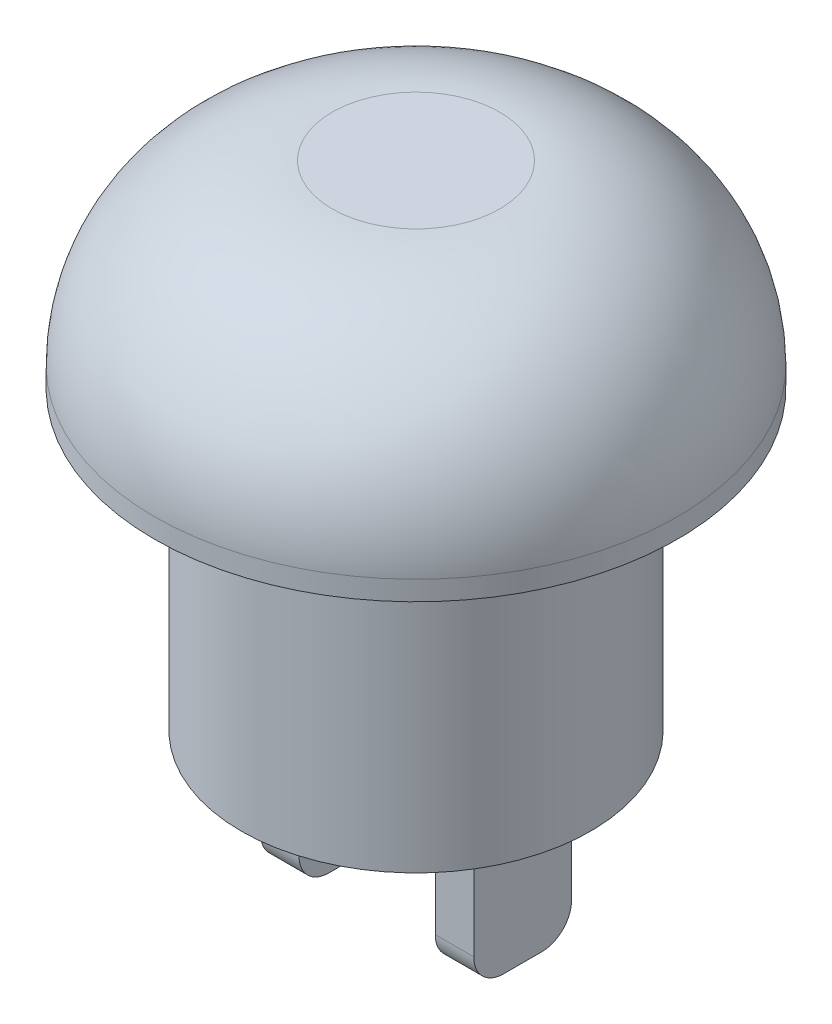
SolidWorks part; units mm, degrees
ref_plane "Plan de face" through (0, 0, 0) normal (0, 0, 1) x (1, 0, 0)
ref_plane "Plan de dessus" through (0, 0, 0) normal (0, 1, 0) x (1, 0, 0)
ref_plane "Plan de droite" through (0, 0, 0) normal (1, 0, 0) x (0, 0, -1)
sketch "Sketch1" plane through (0, 0, 0) normal (0, 1, 0) x (1, 0, 0)
  circle A0 centre (0, 0) radius 5.9
  dimension "D1" = 11.8
extrude "Boss-Extrude1" add sketch "Sketch1" along normal blind 10
sketch "Sketch2" plane through (0, 10, 0) normal (0, 1, 0) x (1, 0, 0)
  circle A0 centre (0, 0) radius 8.83
  dimension "D1" = 17.66
extrude "Boss-Extrude2" add sketch "Sketch2" along normal blind 6.66
fillet "Fillet1" radius 6 1 edges at (0, 16.66, 8.83)
sketch "Sketch3" plane through (0, 0, 0) normal (0, -1, 0) x (1, 0, 0)
  line L0 (-5.9, 0) -> (5.9, 0)
  line L1 (-5.9, 0) -> (0, 0) construction
  line L2 (0, -5.1238) -> (0, 5.1238)
  line L3 (-3.6, -1.65) -> (-2.3, -1.65)
  line L4 (-3.6, -1.65) -> (-3.6, 1.65)
  line L5 (-3.6, 1.65) -> (-2.3, 1.65)
  line L6 (-2.3, -1.65) -> (-2.3, 1.65)
  line L7 (-3.6, -1.65) -> (-2.3, 1.65) construction
  line L8 (-3.6, 1.65) -> (-2.3, -1.65) construction
  line L9 (3.6, 1.65) -> (2.3, 1.65)
  line L10 (2.3, -1.65) -> (2.3, 1.65)
  line L11 (3.6, -1.65) -> (2.3, -1.65)
  line L12 (3.6, -1.65) -> (3.6, 1.65)
  circle A0 centre (0, 0) radius 5.9 construction
  point P0 (-2.95, 0)
  point P7 (0, 0)
  point P16 (0, 0)
  dimension "D1" = 1.3
  dimension "D2" = 3.3
extrude "Boss-Extrude3" add sketch "Sketch3" along normal blind 5 contours L11 L12 L0 L10 | L0 L12 L9 L10 | L0 L6 L5 L4 | L3 L6 L0 L4
fillet "Fillet2" radius 1 4 edges at (2.95, -5, 1.65) (2.95, -5, -1.65) (-2.95, -5, 1.65) (-2.95, -5, -1.65)
